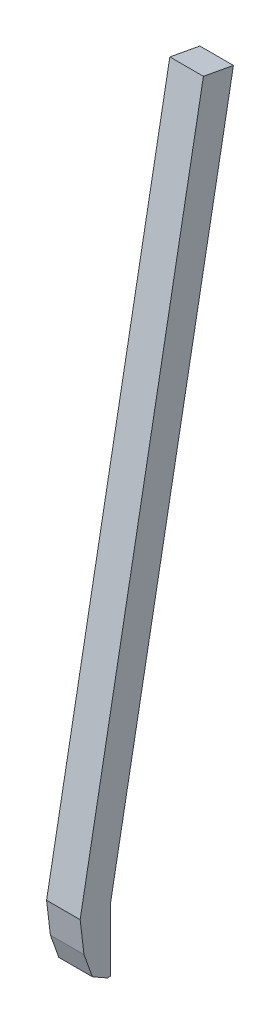
SolidWorks part; units mm, degrees
ref_plane "Front Plane" through (0, 0, 0) normal (0, 0, 1) x (1, 0, 0)
ref_plane "Top Plane" through (0, 0, 0) normal (0, 1, 0) x (1, 0, 0)
ref_plane "Right Plane" through (0, 0, 0) normal (1, 0, 0) x (0, 0, -1)
sketch "Sketch3" plane through (0, 0, 0) normal (0, 0, 1) x (1, 0, 0)
  line L0 (-5.5, -10.5) -> (-5.5, 10.5)
  line L2 (-5.5, 10.5) -> (5.5, 10.5)
  line L3 (5.5, 10.5) -> (5.5, -10.5)
  line L4 (5.5, -10.5) -> (-5.5, -10.5)
  dimension "D1" = 11
  dimension "D2" = 21
  dimension "D3" = 5.5
  dimension "D4" = 10.5
extrude "Boss-Extrude1" add sketch "Sketch3" along normal blind 10
sketch "Sketch5" plane through (0, 0, 0) normal (0, 0, 1) x (1, 0, 0)
  line L0 (0, 0) -> (0, 1.5)
  line L1 (0, 1.5) -> (-2, 1.5)
  line L2 (-2, 1.5) -> (-2, -1.5)
  line L3 (-2, -1.5) -> (2, -1.5)
  line L4 (2, -1.5) -> (2, 1.5)
  line L5 (2, 1.5) -> (0, 1.5)
  dimension "D1" = 2
  dimension "D2" = 4
  dimension "D3" = 3
  dimension "D4" = 1.5
extrude "Cut-Extrude1" cut sketch "Sketch5" along normal blind 8 contours L1 L2 L3 L4 L5
sketch "Sketch6" plane through (0, 0, 0) normal (1, 0, 0) x (0, 0, -1)
  line L1 (-10, -10.5) -> (0, -10.5) construction
  line L2 (-1.0867, -10.5) -> (-6.0116, -7.6935)
  line L3 (-6.0116, -7.6935) -> (-8.7536, 0)
  line L4 (-8.7536, 0) -> (-10, 10.5)
  line L5 (0, 0) -> (-8.7536, 0)
  line L6 (-10, 10.5) -> (-10, -10.5)
  line L8 (-1.0867, -10.5) -> (-1.0867, -10.7607)
  line L9 (-1.0867, -10.7607) -> (-10, -11.3245)
  line L10 (-10, -11.3245) -> (-10, -10.5)
  point P0 (-10, -10.5)
extrude "Cut-Extrude5" cut sketch "Sketch6" against normal blind 8 and the other way blind 8 contours L3 L2 L8 L9 L10 L6 L4
sketch "Sketch7" plane through (0, 0, 0) normal (1, 0, 0) x (0, 0, -1)
  line L0 (0, -10.5) -> (86.8528, 255.9971)
sketch "Sketch18" plane through (0, 0, 0) normal (1, 0, 0) x (0, 0, -1)
  line L0 (0, 10.5) -> (40.1954, 227.6978)
  line L1 (-10, 10.5) -> (0, 10.5)
  line L2 (40.1954, 227.6978) -> (30.3624, 229.5175)
  line L7 (-10, 10.5) -> (30.3624, 229.5175)
  point P3 (-10, 10.5)
  dimension "D2" = 10
extrude "Boss-Extrude2" add sketch "Sketch18" along normal blind 5.5 and the other way blind 5.5
